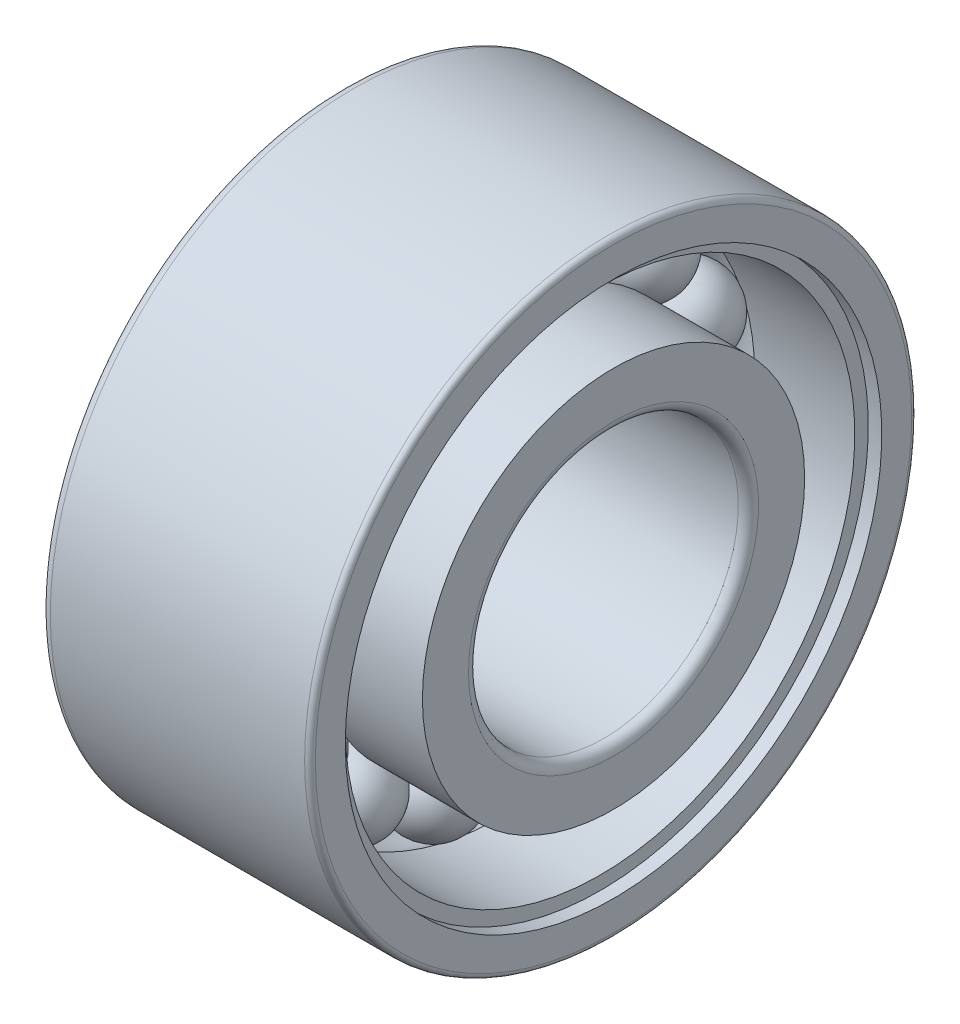
SolidWorks part; units mm, degrees
ref_plane "Front" through (0, 0, 0) normal (0, 0, 1) x (1, 0, 0)
ref_plane "Top" through (0, 0, 0) normal (0, 1, 0) x (1, 0, 0)
ref_plane "Right" through (0, 0, 0) normal (1, 0, 0) x (0, 0, -1)
sketch "Sketch1" plane through (0, 0, 0) normal (0, 0, 1) x (1, 0, 0)
  line L0 (-3.0919, 0) -> (2.899, 0) construction
  line L1 (-3.0919, 3.25) -> (2.899, 3.25) construction
  line L2 (-0.625, 3.25) -> (0.625, 3.25)
  arc A0 (-0.625, 3.25) -> (0.625, 3.25) centre (0, 3.25) ccw
  dimension "R" = 0.625
  dimension "D1" = 3.25
revolve "Revolve1" add sketch "Sketch1" angle 360 about L1
sketch "Sketch2" plane through (0, 0, 0) normal (0, 0, 1) x (1, 0, 0)
  line L0 (-2, 2.8333) -> (-0.4523, 2.8333)
  line L1 (2, 2.8333) -> (2, 2)
  line L2 (2, 2) -> (-2, 2)
  line L3 (-2, 2) -> (-2, 2.8333)
  line L4 (-2.9924, 0) -> (3.9982, 0) construction
  line L5 (-1.8743, 3.25) -> (3.1755, 3.25) construction
  line L7 (0.4523, 2.8333) -> (2, 2.8333)
  line L8 (-2, 6.2861) -> (-2, 1.454) construction
  arc A0 (-0.4523, 2.8333) -> (0.4523, 2.8333) centre (0, 3.25) ccw
  dimension "D1" = 3.25
  dimension "B" = 4
  dimension "D2" = 0.615
  dimension "d" = 4
  dimension "D3" = 5.6667
  dimension "T" = 4
  dimension "D6" = 2
revolve "Revolve2" add sketch "Sketch2" angle 360 about L4
sketch "Sketch3" plane through (0, 0, 0) normal (0, 0, 1) x (1, 0, 0)
  line L0 (-2, 3.6667) -> (-2, 4.5)
  line L1 (-2, 4.5) -> (2, 4.5)
  line L2 (2, 4.5) -> (2, 3.9767)
  line L3 (1.8, 3.7767) -> (0.3176, 3.7767)
  line L4 (-2.9924, 0) -> (3.4329, 0) construction
  line L6 (-1.7375, 3.25) -> (2.2712, 3.25) construction
  line L7 (-0.4523, 3.6667) -> (-2, 3.6667)
  line L8 (1.8, 3.7767) -> (1.8, 3.9767)
  line L9 (1.8, 3.9767) -> (2, 3.9767)
  arc A0 (0.3176, 3.7767) -> (-0.4523, 3.6667) centre (0, 3.25) ccw
  dimension "D1" = 3.25
  dimension "D4" = 0.615
  dimension "B" = 4
  dimension "DD" = 9
  dimension "D3" = 7.5533
  dimension "D5" = 7.3333
  dimension "D6" = 0.2
  dimension "D7" = 0.2
  dimension "D2" = 2
revolve "Revolve3" add sketch "Sketch3" angle 360 about L4
pattern_circular "Circular-Pattern1" count 15 over 360 about axis through (0, 0, 0) along (1, 0, 0) of "Revolve1"
fillet "Fillet1" radius 0.15 2 edges at (2, 0, 2) (-2, 0, 4.5)
fillet "Fillet2" radius 0.08 2 edges at (2, 0, 4.5) (-2, 0, 2)
equation "\"R@Sketch1\" =  ( \"DD@Sketch3\" - \"d@Sketch2\" )  / 8"
equation "\"D1@Sketch1\"=(\"d@Sketch2\"+\"DD@Sketch3\")/4"
equation "\"D1@Sketch2\"=(\"d@Sketch2\"+\"DD@Sketch3\")/4"
equation "\"D3@Sketch2\" =  \"d@Sketch2\"+  ( \"DD@Sketch3\" - \"d@Sketch2\" )  /3"
equation "\"D2@Sketch2\" =  ( \"DD@Sketch3\" - \"d@Sketch2\" )  / 8 - 0.01"
equation "\"D6@Sketch2\" = \"B@Sketch2\" / 2"
equation "\"B@Sketch3\" = \"B@Sketch2\""
equation "\"D2@Sketch3\" = \"B@Sketch3\" / 2"
equation "\"D1@Sketch3\"=(\"d@Sketch2\"+\"DD@Sketch3\")/4"
equation "\"D3@Sketch3\" = (  \"DD@Sketch3\" -  (\"DD@Sketch3\" - \"d@Sketch2\"  )  / 3 )  * 1.03"
equation "\"D5@Sketch3\" = \"DD@Sketch3\" -  (  \"DD@Sketch3\" - \"d@Sketch2\")  / 3"
equation "\"D6@Sketch3\" = \"d@Sketch2\" / 20"
equation "\"D7@Sketch3\"=\"D6@Sketch3\""
equation "\"D4@Sketch3\"=(\"DD@Sketch3\"-\"d@Sketch2\")/8-0.01"
equation "\"m@Circular-Pattern1\" = int( 3.14159265 / atn(\"R@Sketch1\" / sqr((\"d@Sketch2\"+\"DD@Sketch3\")/4 * (\"d@Sketch2\"+\"DD@Sketch3\")/4 - \"R@Sketch1\" *  \"R@Sketch1\")))-1"
